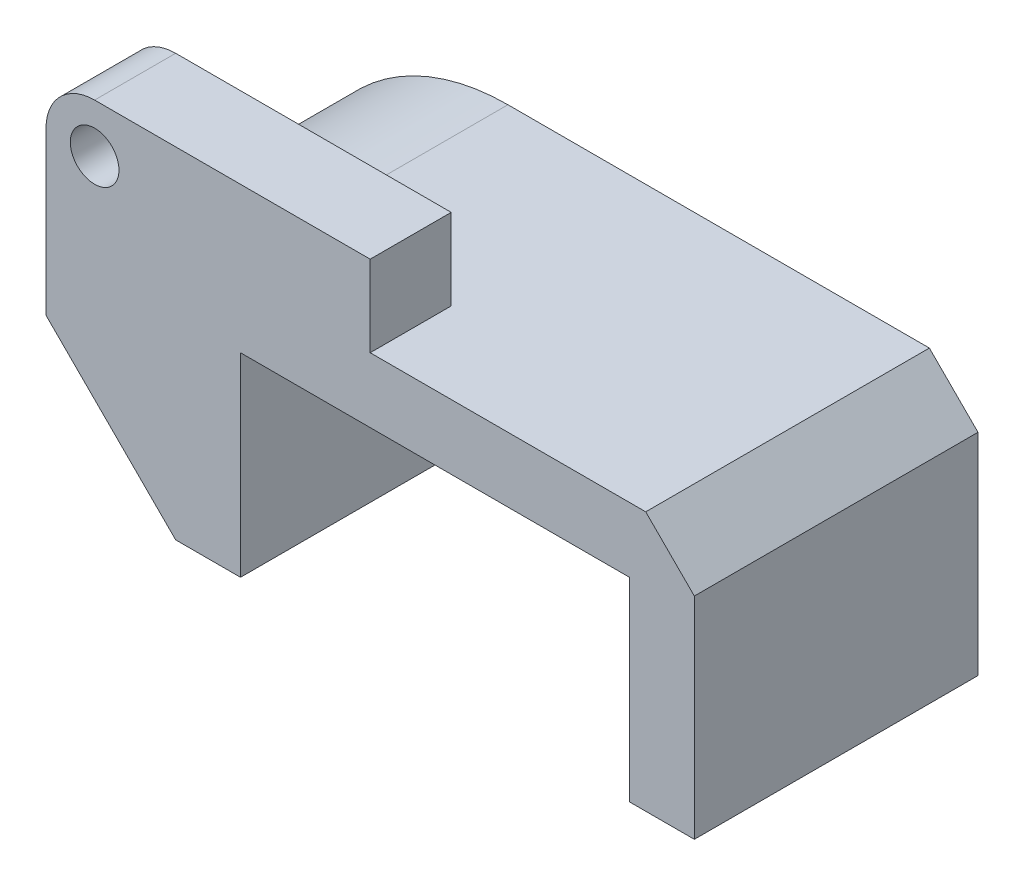
SolidWorks part; units mm, degrees
ref_plane "Front Plane" through (0, 0, 0) normal (0, 0, 1) x (1, 0, 0)
ref_plane "Top Plane" through (0, 0, 0) normal (0, 1, 0) x (1, 0, 0)
ref_plane "Right Plane" through (0, 0, 0) normal (1, 0, 0) x (0, 0, -1)
sketch "Sketch1" plane through (0, 0, 0) normal (0, 0, 1) x (1, 0, 0)
  line L0 (12, -12) -> (16, -12)
  line L1 (-16, 4) -> (16, 4)
  line L2 (-16, 4) -> (-16, -12)
  line L3 (-16, -12) -> (-12, -12)
  line L4 (16, 4) -> (16, -12)
  line L6 (-12, -12) -> (-12, 0)
  line L7 (-12, 0) -> (12, 0)
  line L8 (12, -12) -> (12, 0)
  dimension "D1" = 24
  dimension "D2" = 4
  dimension "D3" = 12
  dimension "D4" = 4
extrude "Boss-Extrude1" add sketch "Sketch1" along normal blind 17.5
chamfer "Chamfer1" distance 3 angle 45 2 edges at (16, 4, 8.75) (-16, 4, 8.75)
sketch "Sketch2" plane through (0, 0, 17.5) normal (0, 0, 1) x (1, 0, 0)
  line L0 (-16, -12) -> (-12, -12) construction
  line L1 (-16, 1) -> (-4, 1)
  line L2 (-16, 9) -> (-16, 1) construction
  line L3 (-16, 9) -> (-4, 9)
  line L4 (-4, 1) -> (-4, 9)
  line L5 (-16, 9) -> (-24, 9)
  line L6 (-16, 1) -> (-16, -12)
  line L7 (-16, -12) -> (-24, -12)
  line L8 (-24, 9) -> (-24, -12)
  dimension "D1" = 12
  dimension "D2" = 8
  dimension "D3" = 8
extrude "Boss-Extrude2" add sketch "Sketch2" against normal blind 5
chamfer "Chamfer2" distance 8 angle 45 1 edges at (-24, -12, 15)
sketch "Sketch3" plane through (0, 0, 17.5) normal (0, 0, 1) x (1, 0, 0)
  line L0 (-4, 9) -> (-24, 9) construction
  line L1 (-24, 9) -> (-24, -4) construction
  circle A0 centre (-21, 6) radius 1.5
  dimension "D1" = 3
  dimension "D3" = 3
  dimension "D2" = 3
extrude "Cut-Extrude1" cut sketch "Sketch3" against normal through all
fillet "Fillet1" radius 3 1 edges at (-24, 9, 15)
sketch "Sketch4" plane through (0, 0, 0) normal (0, 0, -1) x (-1, 0, 0)
  line L0 (14.5, -6) -> (-14.5, -6) construction
  line L1 (0, -6) -> (0, 0) construction
  line L2 (-12, -12) -> (-16, -12) construction
  circle A0 centre (-14.5, -6) radius 1
  circle A1 centre (14.5, -6) radius 1
  dimension "D3" = 2
  dimension "D1" = 29
  dimension "D2" = 6
extrude "Cut-Extrude2" cut sketch "Sketch4" against normal blind 8
sketch "Sketch5" plane through (0, 0, 0) normal (0, 0, -1) x (-1, 0, 0)
  line L0 (13, 4) -> (16, 1)
  line L1 (16, 1) -> (16, -12)
  line L2 (16, -12) -> (24, -4)
  line L3 (13, 4) -> (9.606, 4) construction
  line L4 (-13, 4) -> (13, 4) construction
  line L5 (24, -4) -> (24, -2)
  line L6 (24, 6) -> (24, -4) construction
  arc A0 (13, 4) -> (24, -2) centre (13, -9.0833) cw
  dimension "D1" = 10
extrude "Boss-Extrude3" add sketch "Sketch5" against normal up to surface (12.5 mm away) up to face at (-22.5, 6, 12.5)
